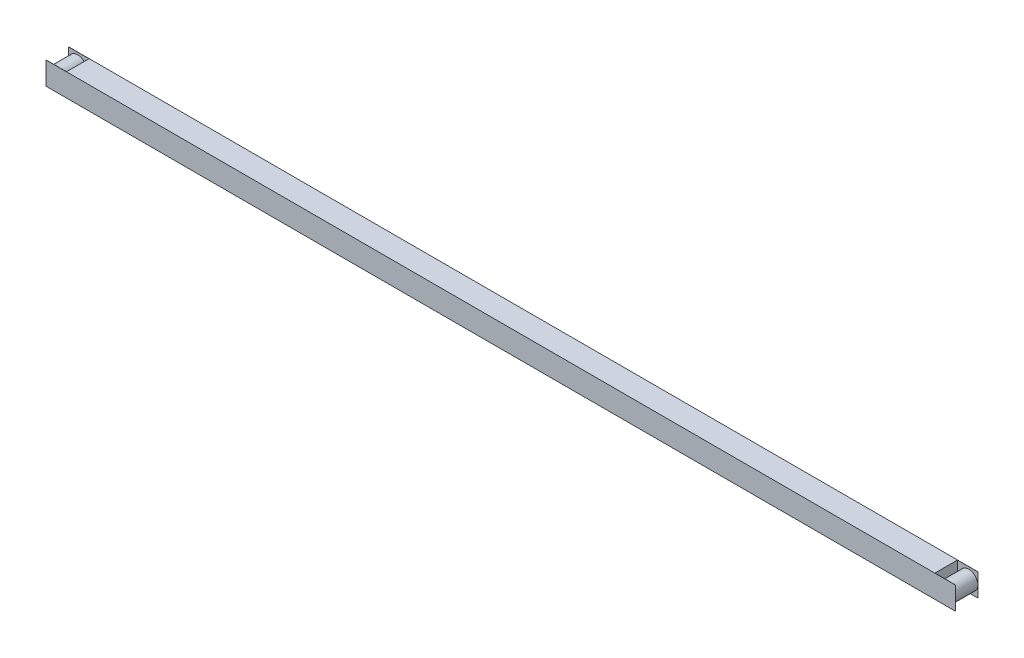
SolidWorks part; units mm, degrees
ref_plane "Front Plane" through (0, 0, 0) normal (0, 0, 1) x (1, 0, 0)
ref_plane "Top Plane" through (0, 0, 0) normal (0, 1, 0) x (1, 0, 0)
ref_plane "Right Plane" through (0, 0, 0) normal (1, 0, 0) x (0, 0, -1)
sketch "Sketch1" plane through (0, 0, 0) normal (0, 0, 1) x (1, 0, 0)
  line L0 (0, 0) -> (200, 0)
  line L1 (200, 0) -> (200, 5)
  line L2 (200, 5) -> (0, 5)
  line L3 (0, 5) -> (0, 0)
  dimension "D1" = 200
  dimension "D2" = 5
extrude "Boss-Extrude1" add sketch "Sketch1" along normal blind 5
ref_plane "Plane1" through (0, 0, 2.5) normal (0, 0, 1) x (1, 0, 0)
sketch "Sketch2" plane through (0, 0, 2.5) normal (0, 0, 1) x (1, 0, 0)
  line L0 (0, 0) -> (200, 0) construction
  line L1 (0, 5) -> (4.5, 5)
  line L2 (0, 5) -> (0, 0)
  line L3 (0, 0) -> (4.5, 0)
  line L4 (4.5, 5) -> (4.5, 0)
  line L5 (200, 5) -> (200, 0)
  line L6 (200, 0) -> (195.5, 0)
  line L7 (195.5, 0) -> (195.5, 5)
  line L8 (200, 5) -> (0, 5) construction
  line L9 (195.5, 5) -> (200, 5)
  dimension "D1" = 5
  dimension "D2" = 4.5
  dimension "D3" = 4.5
extrude "Cut-Extrude1" cut sketch "Sketch2" against normal mid plane 4.95
sketch "Sketch3" plane through (0, 0, 0.025) normal (0, 0, 1) x (1, 0, 0)
  line L8 (0, 5) -> (0, 0) construction
  circle A0 centre (2, 2.5) radius 2
  dimension "D1" = 4
extrude "Boss-Extrude3" add sketch "Sketch3" along normal blind 4.95
sketch "Sketch4" plane through (0, 0, 0.025) normal (0, 0, 1) x (1, 0, 0)
  line L3 (200, 0) -> (200, 5) construction
  circle A0 centre (198, 2.5) radius 2
  dimension "D1" = 4
extrude "Boss-Extrude4" add sketch "Sketch4" along normal blind 4.95
